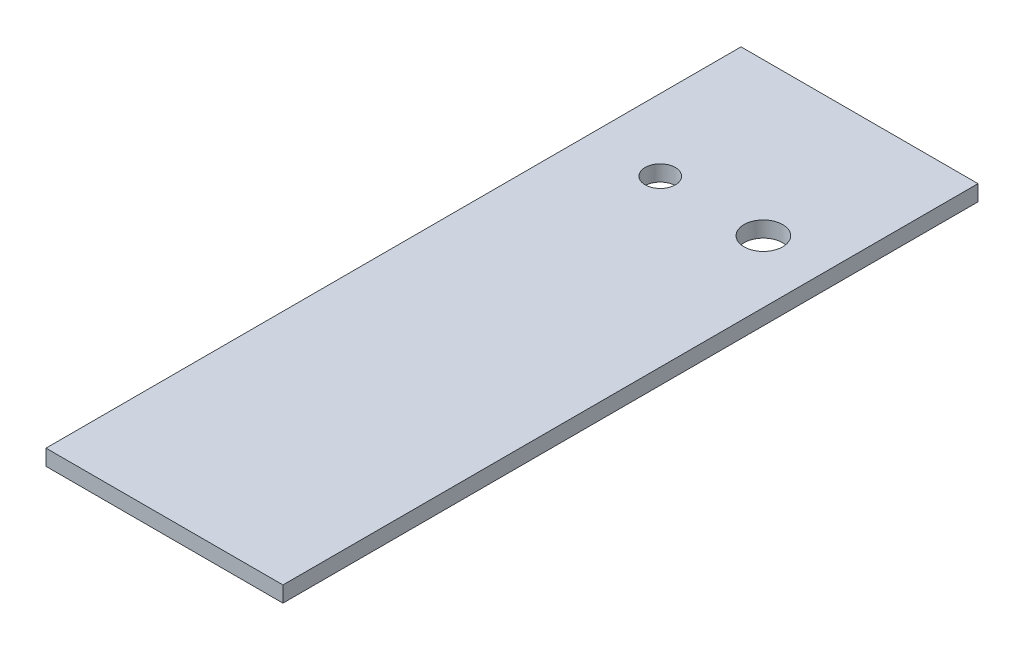
SolidWorks part; units mm, degrees
ref_plane "Front Plane" through (0, 0, 0) normal (0, 0, 1) x (1, 0, 0)
ref_plane "Top Plane" through (0, 0, 0) normal (0, 1, 0) x (1, 0, 0)
ref_plane "Right Plane" through (0, 0, 0) normal (1, 0, 0) x (0, 0, -1)
sketch "Sketch1" plane through (0, 0, 0) normal (0, 1, 0) x (1, 0, 0)
  line L1 (0, 0) -> (95.25, 0)
  line L2 (0, 0) -> (0, -279.4)
  line L3 (0, -279.4) -> (95.25, -279.4)
  line L4 (95.25, 0) -> (95.25, -279.4)
  circle A0 centre (28.7824, -61.2569) radius 6.0685
  circle A1 centre (70.2227, -61.2569) radius 7.77
  dimension "D1" = 95.25
  dimension "D2" = 279.4
extrude "Boss-Extrude1" add sketch "Sketch1" along normal blind 6.35
